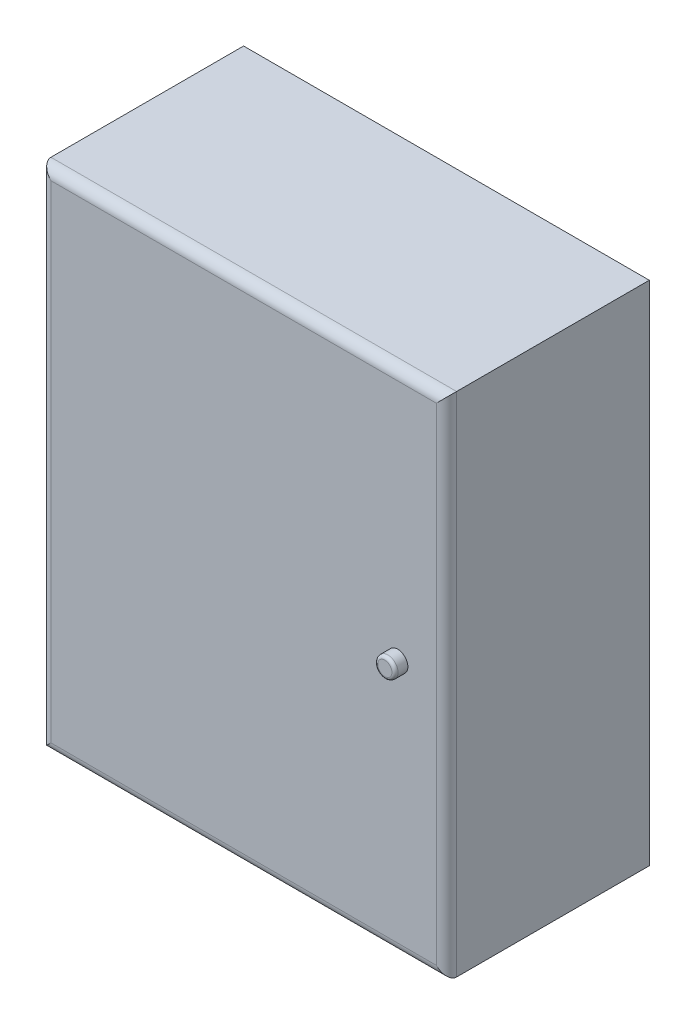
SolidWorks part; units mm, degrees
ref_plane "Front Plane" through (0, 0, 0) normal (0, 0, 1) x (1, 0, 0)
ref_plane "Top Plane" through (0, 0, 0) normal (0, 1, 0) x (1, 0, 0)
ref_plane "Right Plane" through (0, 0, 0) normal (1, 0, 0) x (0, 0, -1)
sketch "Croquis1" plane through (0, 0, 0) normal (0, 0, 1) x (1, 0, 0)
  line L1 (0, 0) -> (400, 0)
  line L2 (0, 0) -> (0, 500)
  line L3 (0, 500) -> (400, 500)
  line L4 (400, 0) -> (400, 500)
  dimension "D1" = 400
  dimension "D2" = 500
extrude "Saliente-Extruir1" add sketch "Croquis1" along normal blind 200
fillet "Redondeo1" radius 10 4 edges at (400, 250, 200) (200, 0, 200) (0, 250, 200) (200, 500, 200)
sketch "Croquis2" plane through (0, 0, 200) normal (0, 0, 1) x (1, 0, 0)
  circle A0 centre (351.9562, 250.9161) radius 10
  dimension "D1" = 20
extrude "Saliente-Extruir2" add sketch "Croquis2" along normal blind 12.7
fillet "Redondeo2" radius 3 1 edges at (361.9562, 250.9161, 212.7)
